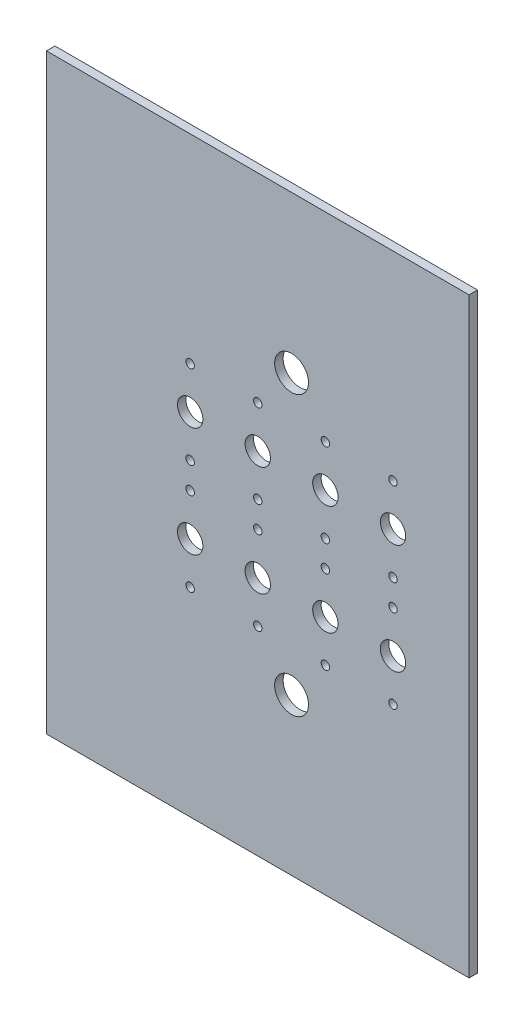
SolidWorks part; units mm, degrees
ref_plane "前视基准面" through (0, 0, 0) normal (0, 0, 1) x (1, 0, 0)
ref_plane "上视基准面" through (0, 0, 0) normal (0, 1, 0) x (1, 0, 0)
ref_plane "右视基准面" through (0, 0, 0) normal (1, 0, 0) x (0, 0, -1)
sketch "草图1" plane through (0, 0, 0) normal (0, 0, 1) x (1, 0, 0)
  line L0 (0, 350) -> (500, 350)
  line L1 (500, 350) -> (500, -350)
  line L2 (500, -350) -> (0, -350)
  line L3 (0, -350) -> (0, 350)
  circle A0 centre (170, 114.5) radius 5
  circle A1 centre (170, 15.5) radius 5
  circle A2 centre (250, 114.5) radius 5
  circle A3 centre (250, 15.5) radius 5
  circle A4 centre (330, 114.5) radius 5
  circle A5 centre (330, 15.5) radius 5
  circle A6 centre (410, 114.5) radius 5
  circle A7 centre (410, 15.5) radius 5
  circle A8 centre (290, 165) radius 20
  circle A9 centre (290, -165) radius 20
  circle A10 centre (170, 65) radius 15
  circle A11 centre (250, 65) radius 15
  circle A12 centre (330, 65) radius 15
  circle A13 centre (410, 65) radius 15
  circle A14 centre (170, -114.5) radius 5
  circle A15 centre (170, -15.5) radius 5
  circle A16 centre (250, -114.5) radius 5
  circle A17 centre (250, -15.5) radius 5
  circle A18 centre (330, -114.5) radius 5
  circle A19 centre (330, -15.5) radius 5
  circle A20 centre (410, -114.5) radius 5
  circle A21 centre (410, -15.5) radius 5
  circle A22 centre (170, -65) radius 15
  circle A23 centre (250, -65) radius 15
  circle A24 centre (330, -65) radius 15
  circle A25 centre (410, -65) radius 15
extrude "凸台-拉伸1" add sketch "草图1" along normal blind 10
